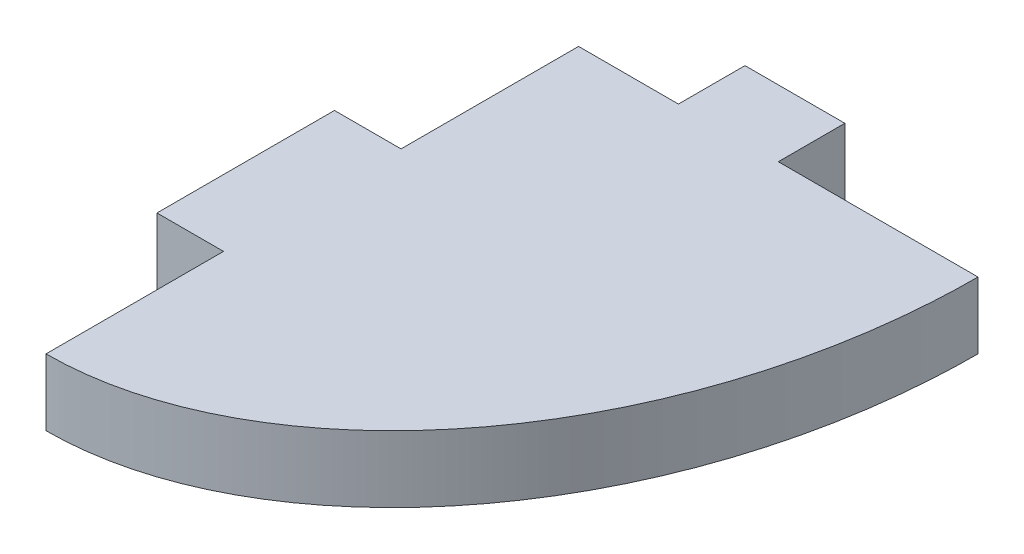
SolidWorks part; units mm, degrees
ref_plane "Front Plane" through (0, 0, 0) normal (0, 0, 1) x (1, 0, 0)
ref_plane "Top Plane" through (0, 0, 0) normal (0, 1, 0) x (1, 0, 0)
ref_plane "Right Plane" through (0, 0, 0) normal (1, 0, 0) x (0, 0, -1)
sketch "Sketch1" plane through (0, 0, 0) normal (0, 1, 0) x (1, 0, 0)
  line L0 (0, 0) -> (0, 16.9333)
  line L1 (0, 16.9333) -> (-6.35, 16.9333)
  line L2 (-6.35, 16.9333) -> (-6.35, 33.8667)
  line L3 (-6.35, 33.8667) -> (0, 33.8667)
  line L4 (0, 33.8667) -> (0, 50.8)
  line L5 (0, 50.8) -> (9.525, 50.8)
  line L6 (9.525, 50.8) -> (9.525, 57.15)
  line L7 (9.525, 57.15) -> (19.05, 57.15)
  line L8 (19.05, 57.15) -> (19.05, 50.8)
  line L9 (19.05, 50.8) -> (38.1, 50.8)
  ellipse E0 centre (0, 50.8) end of major axis (0, 101.6) minor radius 38.1 (0, 0) -> (38.1, 50.8) ccw
  dimension "D1" = 16.9333
  dimension "D2" = 16.9333
  dimension "D3" = 16.9333
  dimension "D4" = 9.525
  dimension "D5" = 9.525
  dimension "D6" = 19.05
  dimension "D7" = 6.35
  dimension "D8" = 6.35
extrude "Boss-Extrude1" add sketch "Sketch1" along normal blind 6.35 contours L5 L6 L7 L8 L9 E0 L0 L1 L2 L3 L4
equation "\"Plywood Thickness Extra\"=0.25"
equation "\"D1@Boss-Extrude1\"=\"Plywood Thickness Extra\""
equation "\"D8@Sketch1\"=\"Plywood Thickness Extra\""
equation "\"D7@Sketch1\"=\"Plywood Thickness Extra\""
